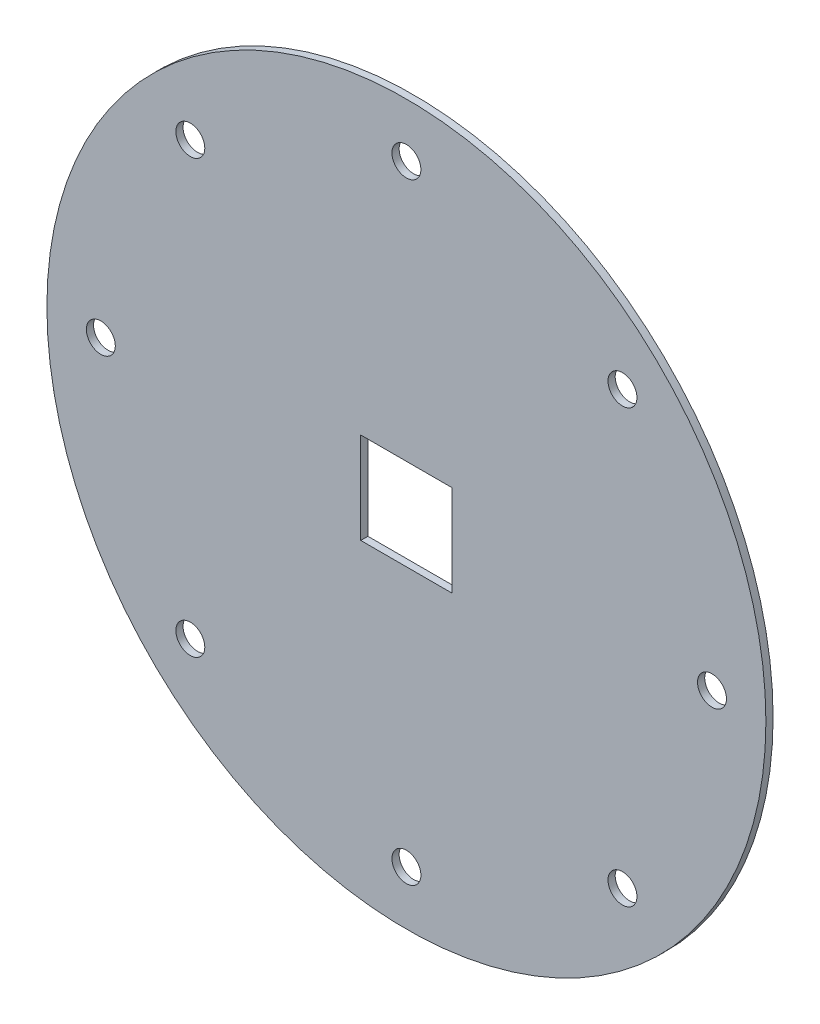
SolidWorks part; units mm, degrees
ref_plane "Alzado" through (0, 0, 0) normal (0, 0, 1) x (1, 0, 0)
ref_plane "Planta" through (0, 0, 0) normal (0, 1, 0) x (1, 0, 0)
ref_plane "Vista lateral" through (0, 0, 0) normal (1, 0, 0) x (0, 0, -1)
sketch "Croquis1" plane through (0, 0, 0) normal (0, 0, 1) x (1, 0, 0)
  line L1 (-12.7, 12.7) -> (12.7, 12.7)
  line L2 (-12.7, 12.7) -> (-12.7, -12.7)
  line L3 (-12.7, -12.7) -> (12.7, -12.7)
  line L4 (12.7, 12.7) -> (12.7, -12.7)
  circle A0 centre (0, 0) radius 100
  circle A1 centre (0, 85) radius 4.025
  circle A2 centre (60.1041, 60.1041) radius 4.025
  circle A3 centre (85, 0) radius 4.025
  circle A4 centre (60.1041, -60.1041) radius 4.025
  circle A5 centre (0, -85) radius 4.025
  circle A6 centre (-60.1041, -60.1041) radius 4.025
  circle A7 centre (-85, 0) radius 4.025
  circle A8 centre (-60.1041, 60.1041) radius 4.025
  point P22 (0, 0)
  point P24 (0, 12.7)
  point P25 (-12.7, 0)
  dimension "D1" = 200
  dimension "D2" = 8.05
  dimension "D3" = 85
  dimension "D5" = 25.4
  dimension "D4" = 8
extrude "Saliente-Extruir1" add sketch "Croquis1" along normal blind 2
